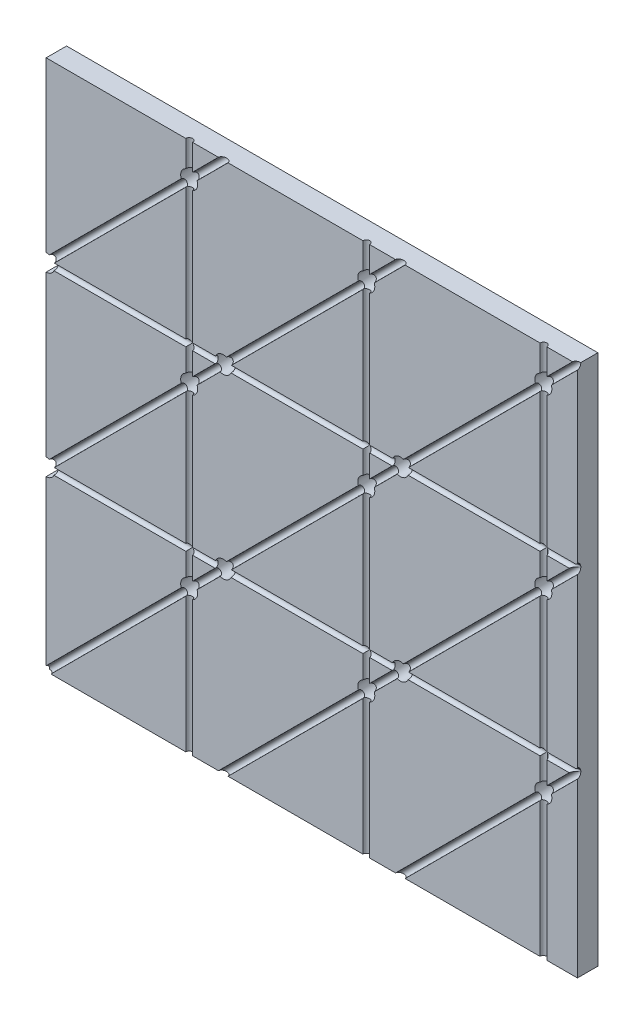
SolidWorks part; units mm, degrees
ref_plane "Front Plane" through (0, 0, 0) normal (0, 0, 1) x (1, 0, 0)
ref_plane "Top Plane" through (0, 0, 0) normal (0, 1, 0) x (1, 0, 0)
ref_plane "Right Plane" through (0, 0, 0) normal (1, 0, 0) x (0, 0, -1)
sketch "Sketch1" plane through (0, 0, 0) normal (0, 0, 1) x (1, 0, 0)
  line L1 (0, 0) -> (156, 0)
  line L2 (0, 0) -> (0, -156)
  line L3 (0, -156) -> (156, -156)
  line L4 (156, 0) -> (156, -156)
  dimension "D1" = 156
extrude "Boss-Extrude1" add sketch "Sketch1" along normal blind 6
sketch "Sketch2" plane through (0, 0, 6) normal (0, 0, 1) x (1, 0, 0)
  line L0 (52, -52) -> (104, -52)
  line L1 (0, 0) -> (52, 0)
  line L2 (0, 0) -> (0, -52)
  line L3 (0, -52) -> (52, -52)
  line L4 (52, 0) -> (52, -52)
  line L5 (104, 0) -> (104, -52)
  line L6 (104, -52) -> (156, -52)
  line L7 (156, 0) -> (156, -52)
  line L8 (0, -104) -> (52, -104)
  line L9 (52, -52) -> (52, -104)
  line L10 (52, -104) -> (104, -104)
  line L11 (104, -52) -> (104, -104)
  line L12 (104, -104) -> (156, -104)
  line L13 (0, -156) -> (52, -156)
  line L14 (52, -104) -> (52, -156)
  line L15 (52, -156) -> (104, -156)
  line L16 (104, -104) -> (104, -156)
  line L17 (104, -156) -> (156, -156)
  line L18 (0, -156) -> (156, 0)
  line L19 (104, -156) -> (156, -104)
  line L20 (0, -52) -> (52, 0)
  line L22 (156, -52) -> (52, -156)
  line L23 (104, 0) -> (0, -104)
  dimension "D1" = 52
  dimension "D2" = 3
  dimension "D3" = 52
  dimension "D5" = 52
  dimension "D4" = 3
sketch "Sketch3" plane through (0, -156, 0) normal (0, -1, 0) x (1, 0, 0)
  line L3 (52, 6) -> (104, 6) construction
  line L4 (52, 6) -> (104, 6)
  circle A0 centre (52, 6) radius 1
  circle A1 centre (104, 6) radius 1
  dimension "D1" = 2
  dimension "D2" = 2
sketch "Sketch4" plane through (0, 0, 0) normal (-1, 0, 0) x (0, 0, 1)
  line L0 (6, -52) -> (6, -104) construction
  line L1 (6, -52) -> (6, -104)
  circle A0 centre (6, -52) radius 1
  circle A1 centre (6, -104) radius 1
  dimension "D1" = 2
  dimension "D2" = 2
extrude "Cut-Extrude2" cut sketch "Sketch4" against normal through all contours A0 | A1
ref_plane "Plane1" through (-78, -78, 0) normal (0.7071, 0.7071, 0) x (0.7071, -0.7071, 0)
sketch "Sketch6" plane through (-78, -78, 0) normal (0.7071, 0.7071, 0) x (0.7071, -0.7071, 0)
  line L0 (36.7696, -6) -> (73.5391, -6) construction
  line L1 (147.0782, -6) -> (183.8478, -6) construction
  line L2 (110.3087, -6) -> (147.0782, -6) construction
  line L3 (73.5391, -6) -> (110.3087, -6) construction
  line L4 (36.7696, -6) -> (73.5391, -6)
  line L5 (147.0782, -6) -> (183.8478, -6)
  line L6 (110.3087, -6) -> (147.0782, -6)
  line L7 (73.5391, -6) -> (110.3087, -6)
  circle A0 centre (73.5391, -6) radius 1
  circle A1 centre (36.7696, -6) radius 1
  circle A2 centre (110.3087, -6) radius 1
  circle A3 centre (147.0782, -6) radius 1
  circle A4 centre (183.8478, -6) radius 1
  dimension "D1" = 2
  dimension "D2" = 2
  dimension "D3" = 2
  dimension "D4" = 2
  dimension "D5" = 2
extrude "Cut-Extrude3" cut sketch "Sketch6" along normal through all contours A1 | A0 | A2 | A3 | A4
sketch "Sketch7" plane through (0, -156, 0) normal (0, -1, 0) x (1, 0, 0)
  line L0 (0, 6) -> (52, 6) construction
  line L2 (0, 6) -> (52, 6)
  circle A0 centre (42, 6) radius 1
  circle A1 centre (94, 6) radius 1
  circle A2 centre (146, 6) radius 1
  dimension "D1" = 2
  dimension "D2" = 10
  dimension "D3" = 3
extrude "Cut-Extrude4" cut sketch "Sketch7" against normal through all contours A0 | A1 | A2
sketch "Sketch8" plane through (0, 0, 6) normal (0, 0, 1) x (1, 0, 0)
  line L0 (104, 0) -> (0, -104) construction
  circle A0 centre (42, -10) radius 2.5
  circle A2 centre (52, -52) radius 2.5
  circle A3 centre (42, -62) radius 2.5
  circle A4 centre (94, -62) radius 2.5
  circle A6 centre (104, -52) radius 2.5
  circle A8 centre (104, -104) radius 2.5
  circle A9 centre (94, -114) radius 2.5
  circle A10 centre (42, -114) radius 2.5
  circle A12 centre (52, -104) radius 2.5
  circle A14 centre (146, -62) radius 2.5
  circle A16 centre (146, -10) radius 2.5
  circle A17 centre (94, -10) radius 2.5
  circle A19 centre (146, -114) radius 2.5
  circle A20 centre (0, -52) radius 2.5
  circle A21 centre (0, -104) radius 2.5
  point P0 (104, 0)
  point P2 (52, 0)
  point P4 (52, -156)
  point P6 (104, -156)
  dimension "D1" = 5
  dimension "D3" = 5
  dimension "D4" = 5
  dimension "D5" = 5
  dimension "D6" = 5
  dimension "D7" = 5
  dimension "D8" = 5
  dimension "D9" = 5
  dimension "D10" = 5
  dimension "D11" = 5
  dimension "D13" = 5
  dimension "D15" = 5
  dimension "D17" = 5
  dimension "D18" = 5
  dimension "D20" = 5
extrude "Cut-Extrude5" cut sketch "Sketch8" against normal through all
